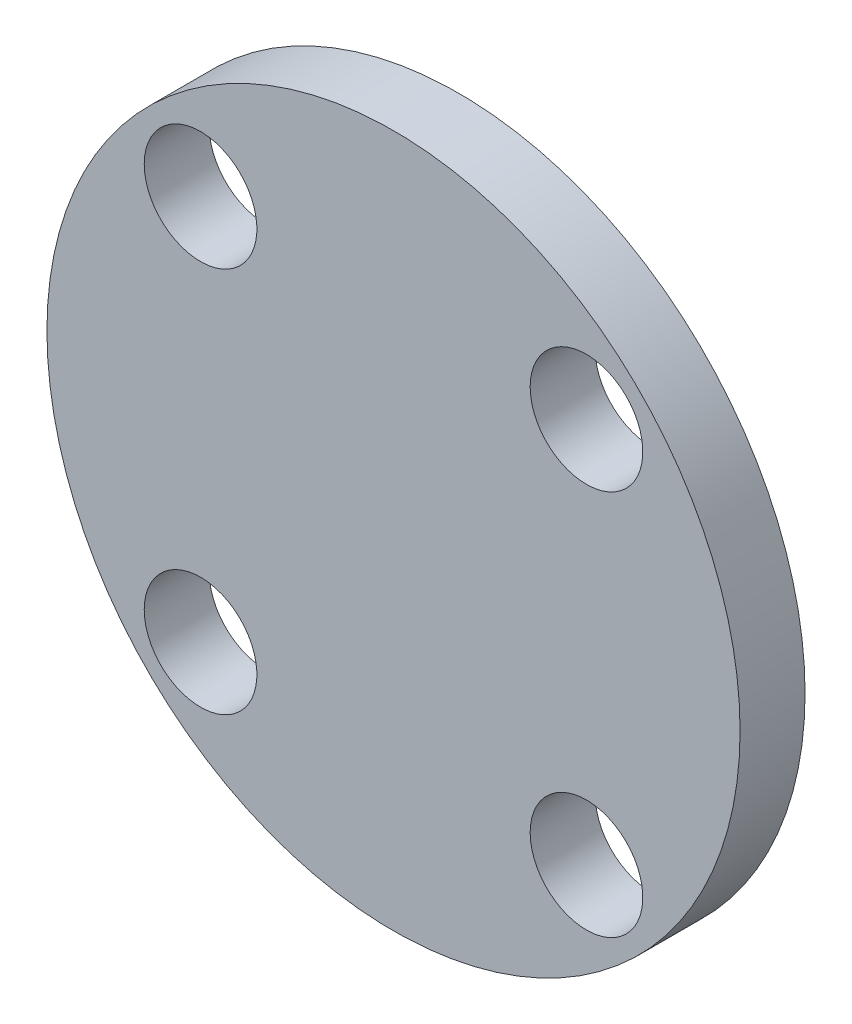
SolidWorks part; units mm, degrees
ref_plane "Front Plane" through (0, 0, 0) normal (0, 0, 1) x (1, 0, 0)
ref_plane "Top Plane" through (0, 0, 0) normal (0, 1, 0) x (1, 0, 0)
ref_plane "Right Plane" through (0, 0, 0) normal (1, 0, 0) x (0, 0, -1)
sketch "Sketch2" plane through (0, 0, 0) normal (0, 0, 1) x (1, 0, 0)
  line L8 (-28.2842, 28.2842) -> (28.2842, 28.2842) construction
  line L9 (28.2842, 28.2842) -> (28.2842, -28.2842) construction
  line L10 (28.2842, -28.2842) -> (-28.2842, -28.2842) construction
  line L11 (-28.2842, -28.2842) -> (-28.2842, 28.2842) construction
  line L12 (0, 50.8) -> (0, -50.8) construction
  line L13 (50.8, 0) -> (-50.8, 0) construction
  circle A0 centre (0, 0) radius 50.8
  circle A13 centre (-28.2842, 28.2842) radius 8.255
  circle A14 centre (28.2842, 28.2842) radius 8.255
  circle A15 centre (28.2842, -28.2842) radius 8.255
  circle A16 centre (-28.2842, -28.2842) radius 8.255
  point P15 (0, 28.2842)
  point P16 (28.2842, 0)
  dimension "D1" = 101.6
  dimension "D6" = 16.51
  dimension "D2" = 56.5684
  dimension "D3" = 56.5684
  dimension "D4" = 56.5684
  dimension "D5" = 56.5684
extrude "Boss-Extrude2" add sketch "Sketch2" along normal blind 9.525
